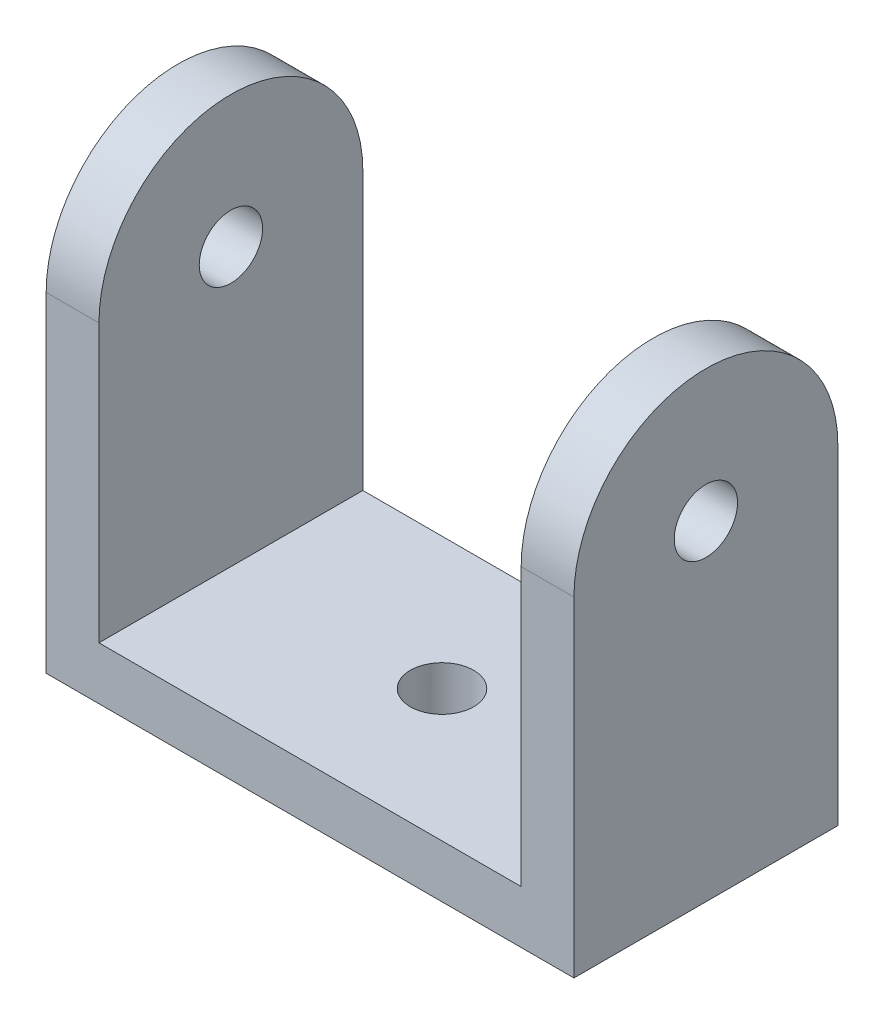
SolidWorks part; units mm, degrees
material "ABS"
ref_plane "Front Plane" through (0, 0, 0) normal (0, 0, 1) x (1, 0, 0)
ref_plane "Top Plane" through (0, 0, 0) normal (0, 1, 0) x (1, 0, 0)
ref_plane "Right Plane" through (0, 0, 0) normal (1, 0, 0) x (0, 0, -1)
sketch "Sketch1" plane through (0, 0, 0) normal (1, 0, 0) x (0, 0, -1)
  line L0 (10, 0) -> (10, -25)
  line L1 (10, -25) -> (-10, -25)
  line L2 (-10, -25) -> (-10, 0)
  arc A0 (-10, 0) -> (10, 0) centre (0, 0) cw
  dimension "D1" = 10
  dimension "D2" = 25
extrude "shoulder" add sketch "Sketch1" along normal mid plane 40
shell "shell" thickness 4
sketch "Sketch2" plane through (20, 0, 0) normal (1, 0, 0) x (0, 0, -1)
  circle A0 centre (0, 0) radius 2.4
  dimension "D1" = 4.8
extrude "pivot holes" cut sketch "Sketch2" against normal through all
sketch "Sketch4" plane through (0, -25, 0) normal (0, -1, 0) x (1, 0, 0)
  circle A0 centre (0, 0) radius 2.4
  dimension "D1" = 4.8
extrude "base mount" cut sketch "Sketch4" against normal up to next and the other way through all
equation "\"D1@Sketch2\"=2*2.4mm"
equation "\"D1@Sketch4\"=2*2.4mm"
